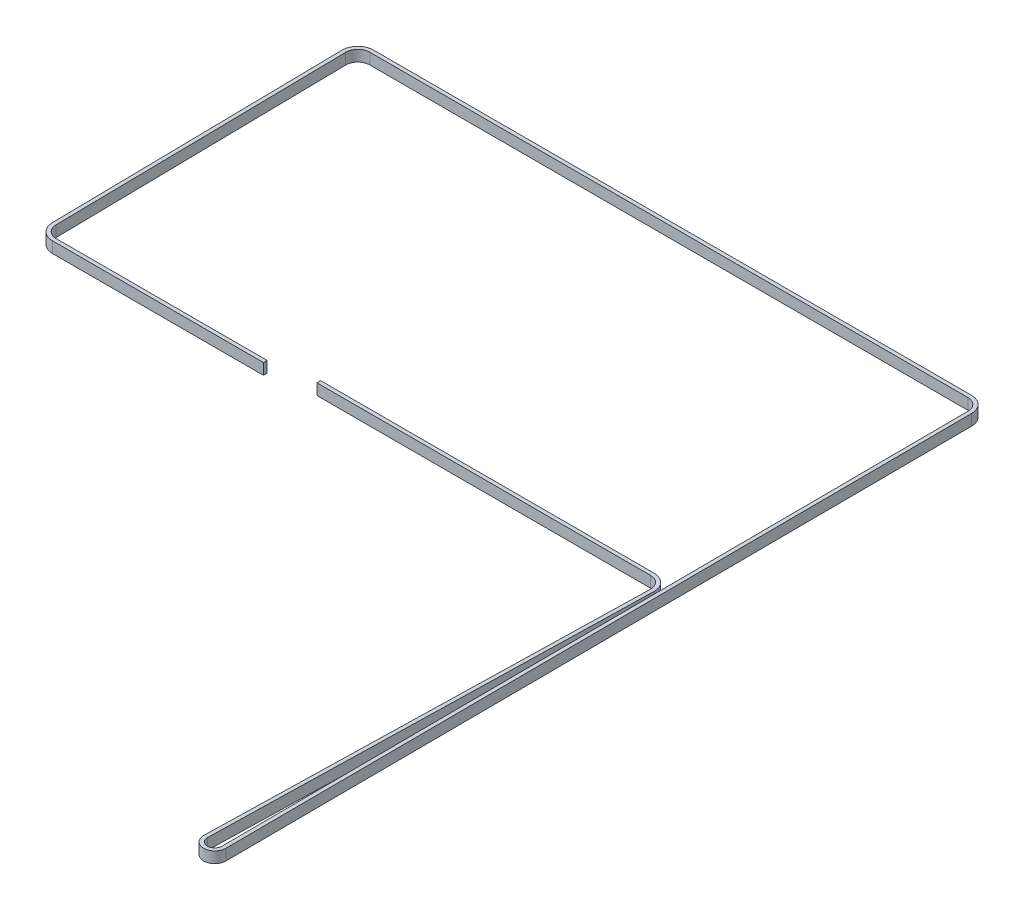
SolidWorks part; units mm, degrees
ref_plane "Front Plane" through (0, 0, 0) normal (0, 0, 1) x (1, 0, 0)
ref_plane "Top Plane" through (0, 0, 0) normal (0, 1, 0) x (1, 0, 0)
ref_plane "Right Plane" through (0, 0, 0) normal (1, 0, 0) x (0, 0, -1)
sketch "Sketch1" plane through (0, 494, 0) normal (0, 1, 0) x (1, 0, 0)
  line L0 (-159.5, 17.0774) -> (-45.1925, 17.0774) construction
  line L1 (-170.499, 184.8667) -> (-167.999, 25.4441) construction
  line L2 (162, 193.5) -> (-162, 193.5) construction
  line L3 (172.4999, -220.9704) -> (170.4999, 185.0419) construction
  line L4 (165.9982, 15.4262) -> (160.5016, -220.8605) construction
  line L5 (159.5, 22.0774) -> (-21.1925, 22.0774) construction
  line L6 (-159.5, 17.0774) -> (-45.1925, 17.0774)
  line L7 (-170.499, 184.8667) -> (-167.999, 25.4441)
  line L8 (162, 193.5) -> (-162, 193.5)
  line L9 (172.4999, -220.9704) -> (170.4999, 185.0419)
  line L10 (165.9982, 15.4262) -> (160.5016, -220.8605)
  line L11 (159.5, 22.0774) -> (-21.1925, 22.0774)
  arc A0 (-167.999, 25.4441) -> (-159.5, 17.0774) centre (-159.5, 25.5774) ccw construction
  arc A1 (-162, 193.5) -> (-170.499, 184.8667) centre (-162, 185) ccw construction
  arc A2 (170.4999, 185.0419) -> (162, 193.5) centre (162, 185) ccw construction
  arc A3 (160.5016, -220.8605) -> (172.4999, -220.9704) centre (166.5, -221) ccw construction
  arc A4 (165.9982, 15.4262) -> (159.5, 22.0774) centre (159.5, 15.5774) ccw construction
  arc A5 (-167.999, 25.4441) -> (-159.5, 17.0774) centre (-159.5, 25.5774) ccw
  arc A6 (-162, 193.5) -> (-170.499, 184.8667) centre (-162, 185) ccw
  arc A7 (170.4999, 185.0419) -> (162, 193.5) centre (162, 185) ccw
  arc A8 (160.5016, -220.8605) -> (172.4999, -220.9704) centre (166.5, -221) ccw
  arc A9 (165.9982, 15.4262) -> (159.5, 22.0774) centre (159.5, 15.5774) ccw
extrude "Extrude-Thin1" add sketch "Sketch1" along normal blind 5 and the other way blind 1 thin thin type one direction wall 2
